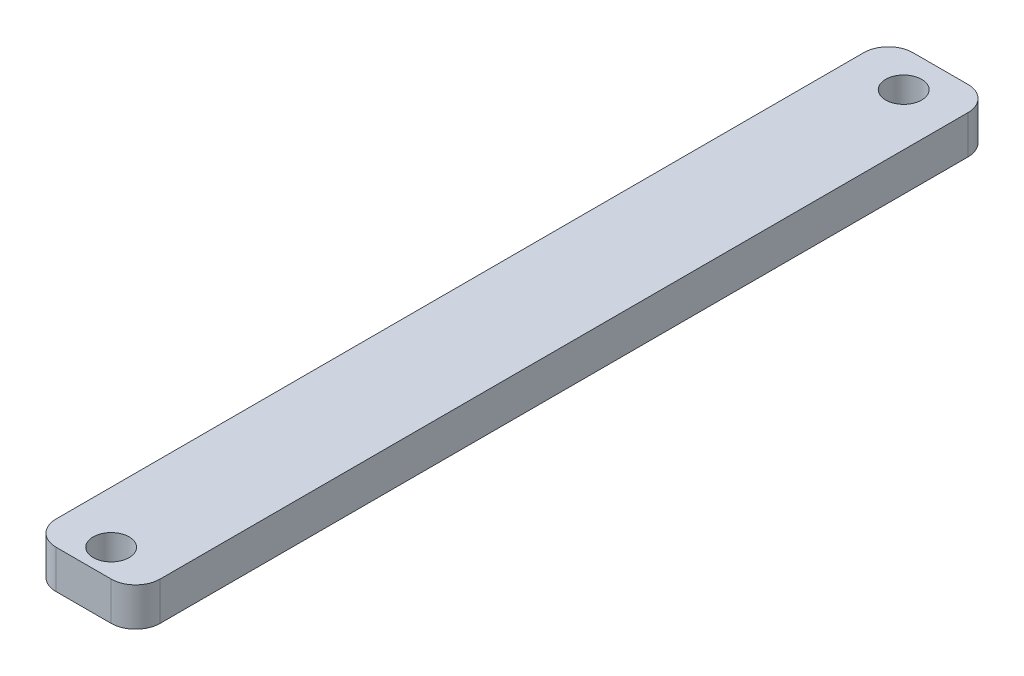
SolidWorks part; units mm, degrees
ref_plane "Front Plane" through (0, 0, 0) normal (0, 0, 1) x (1, 0, 0)
ref_plane "Top Plane" through (0, 0, 0) normal (0, 1, 0) x (1, 0, 0)
ref_plane "Right Plane" through (0, 0, 0) normal (1, 0, 0) x (0, 0, -1)
sketch "Sketch1" plane through (0, 0, 0) normal (0, 1, 0) x (1, 0, 0)
  line L4 (12.5, 2) -> (12.5, -2)
  line L5 (-12.5, 2) -> (12.5, -2) construction
  line L6 (-12.5, -2) -> (12.5, 2) construction
  line L11 (-8.5, 2) -> (12.5, 2)
  line L14 (-4, -2) -> (12.5, -2)
  line L18 (-4, -2) -> (-4, -68)
  line L21 (-4, -68) -> (-12.5, -68)
  line L22 (-12.5, 2) -> (-12.5, -68)
  line L24 (-8.5, 2) -> (-12.5, 2)
  point P0 (0, 0)
  dimension "D1" = 4
  dimension "D3" = 4
  dimension "D2" = 25
  dimension "D4" = 8.5
  dimension "D7" = 70
extrude "Boss-Extrude1" add sketch "Sketch1" along normal blind 3.14
sketch "Sketch7" plane through (0, 3.14, 0) normal (0, 1, 0) x (1, 0, 0)
  line L0 (-12.5, -68) -> (-4, -68) construction
  line L1 (-12.5, 2) -> (-12.5, -68) construction
  circle A0 centre (-8.25, -65.75) radius 1.47
  dimension "D2" = 2.94
  dimension "D1" = 2.25
  dimension "D3" = 4.25
extrude "Cut-Extrude1" cut sketch "Sketch7" against normal through all
ref_plane "Plane1" through (12.5, 3.14, 2) normal (1, 0, 0) x (0, 0, -1)
sketch "Sketch8" plane through (0, 0, 0) normal (0, -1, 0) x (1, 0, 0)
  line L1 (12.5, 2) -> (-4, 2)
  line L2 (12.5, 2) -> (12.5, -2)
  line L3 (12.5, -2) -> (-4, -2)
  line L4 (-4, 2) -> (-4, -2)
  line L5 (-4, 68) -> (-4, 2) construction
  dimension "D1" = 0
extrude "Cut-Extrude2" cut sketch "Sketch8" against normal through all
fillet "Fillet1" radius 2 4 edges at (-12.5, 1.57, 68) (-4, 1.57, 68) (-4, 1.57, -2) (-12.5, 1.57, -2)
sketch "Sketch9" plane through (0, 0, 0) normal (0, -1, 0) x (1, 0, 0)
  line L0 (-8.25, -2) -> (-8.25, 68) construction
  line L1 (-6, -2) -> (-10.5, -2) construction
  line L2 (-10.5, 68) -> (-6, 68) construction
  circle A0 centre (-8.25, 1) radius 1.47
  dimension "D1" = 2.94
  dimension "D2" = 3
extrude "Cut-Extrude3" cut sketch "Sketch9" against normal through all
